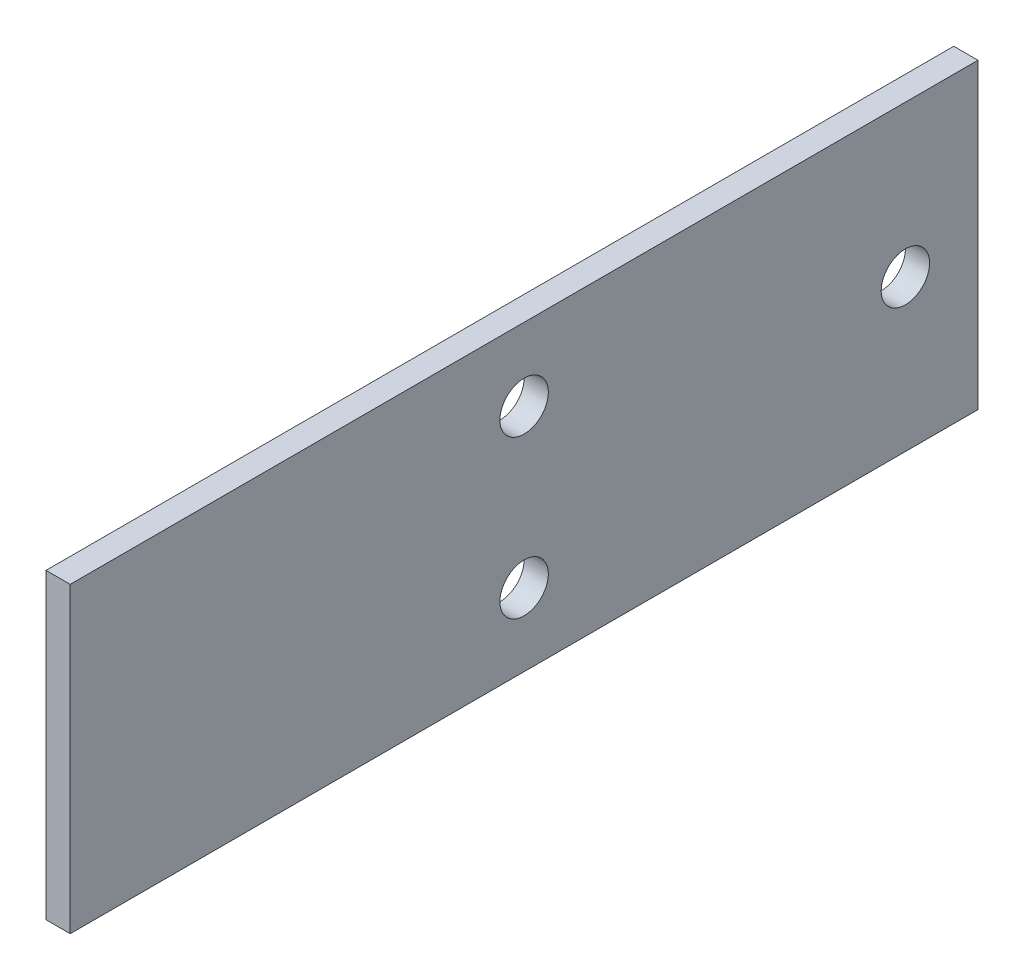
SolidWorks part; units mm, degrees
material "Galvanized Steel"
ref_plane "Front Plane" through (0, 0, 0) normal (0, 0, 1) x (1, 0, 0)
ref_plane "Top Plane" through (0, 0, 0) normal (0, 1, 0) x (1, 0, 0)
ref_plane "Right Plane" through (0, 0, 0) normal (1, 0, 0) x (0, 0, -1)
sketch "Sketch1" plane through (0, 0, 0) normal (0, 1, 0) x (1, 0, 0)
  line L1 (2, -75) -> (-2, -75)
  line L2 (2, -75) -> (2, 75)
  line L3 (2, 75) -> (-2, 75)
  line L4 (-2, -75) -> (-2, 75)
  line L5 (2, -75) -> (-2, 75) construction
  line L6 (2, 75) -> (-2, -75) construction
  point P0 (0, 0)
  dimension "D1" = 4
  dimension "D2" = 150
extrude "Boss-Extrude1" add sketch "Sketch1" along normal blind 50
sketch "Sketch2" plane through (-2, 0, 0) normal (-1, 0, 0) x (0, 0, 1)
  line L0 (-75, 50) -> (75, 50) construction
  line L1 (-75, 0) -> (75, 0) construction
  line L2 (-75, 50) -> (-75, 0) construction
  circle A0 centre (0, 38) radius 4
  circle A1 centre (0, 12) radius 4
  circle A2 centre (-63, 25) radius 4
  dimension "D1" = 12
  dimension "D2" = 12
  dimension "D3" = 8
  dimension "D4" = 8
  dimension "D5" = 8
  dimension "D6" = 12
  dimension "D7" = 25
extrude "Cut-Extrude1" cut sketch "Sketch2" against normal blind 10
